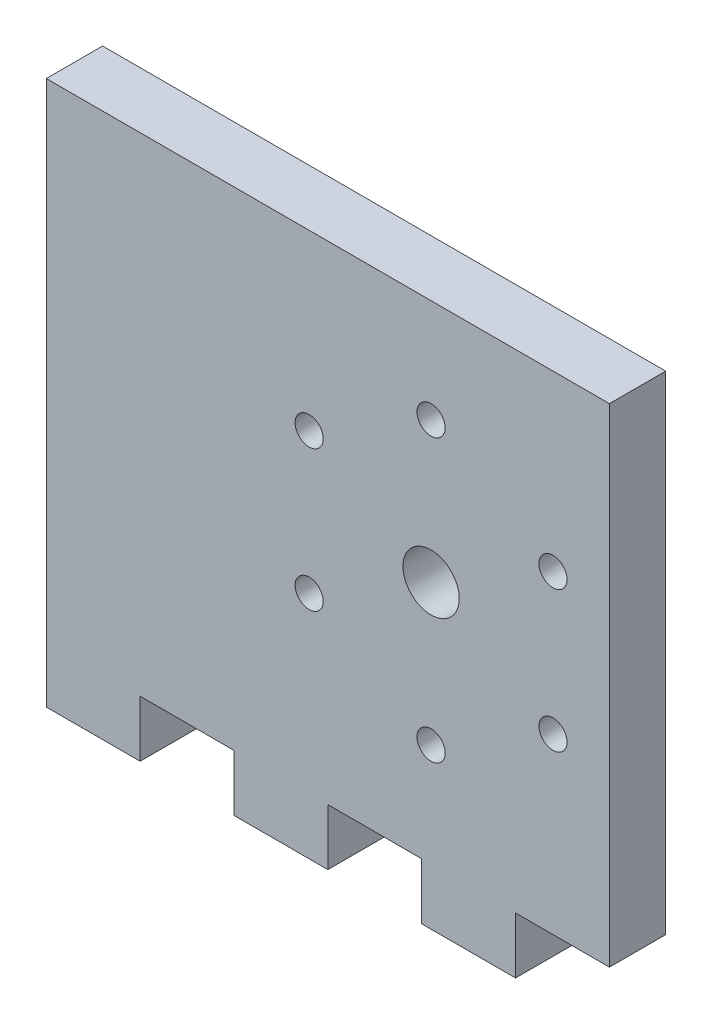
SolidWorks part; units mm, degrees
ref_plane "Alzado" through (0, 0, 0) normal (0, 0, 1) x (1, 0, 0)
ref_plane "Planta" through (0, 0, 0) normal (0, 1, 0) x (1, 0, 0)
ref_plane "Vista lateral" through (0, 0, 0) normal (1, 0, 0) x (0, 0, -1)
sketch "Sketch1" plane through (0, 0, 0) normal (0, 0, 1) x (1, 0, 0)
  line L0 (10, 0) -> (10, 3)
  line L1 (0, 0) -> (10, 0)
  line L2 (0, 0) -> (0, -29)
  line L3 (20.5, 0) -> (20.5, -26) construction
  line L4 (30, 0) -> (30, -26)
  line L5 (0, 0) -> (30, -26) construction
  line L6 (20.5, -13) -> (30, -13) construction
  line L7 (10, 3) -> (15, 3)
  line L8 (15, 3) -> (15, 0)
  line L9 (20, 0) -> (20, 3)
  line L10 (20, 3) -> (25, 3)
  line L11 (25, 3) -> (25, 0)
  line L12 (10, -26) -> (10, -29)
  line L13 (10, -29) -> (15, -29)
  line L14 (15, -29) -> (15, -26)
  line L15 (20, -29) -> (25, -29)
  line L16 (25, -29) -> (25, -26)
  line L17 (20, -29) -> (20, -26)
  line L18 (15, 0) -> (20, 0)
  line L19 (25, 0) -> (30, 0)
  line L20 (25, -26) -> (30, -26)
  line L21 (15, -26) -> (20, -26)
  line L23 (0, -29) -> (5, -29)
  line L24 (5, -29) -> (5, -26)
  line L25 (5, -26) -> (10, -26)
  circle A0 centre (20.5, -13) radius 7.5 construction
  circle A1 centre (20.5, -5.5) radius 0.75
  circle A2 centre (26.9952, -9.25) radius 0.75
  circle A3 centre (26.9952, -16.75) radius 0.75
  circle A4 centre (20.5, -20.5) radius 0.75
  circle A5 centre (14.0048, -16.75) radius 0.75
  circle A6 centre (14.0048, -9.25) radius 0.75
  circle A7 centre (20.5, -13) radius 1.5
  point P0 (0, 0)
  point P43 (20.5, -13)
  dimension "D7" = 15
  dimension "D8" = 1.5
  dimension "D10" = 3
  dimension "D1" = 30
  dimension "D2" = 5
  dimension "D3" = 3
  dimension "D4" = 29
  dimension "D5" = 3
  dimension "D6" = 9.5
  dimension "D9" = 6
extrude "Boss-Extrude1" add sketch "Sketch1" along normal blind 3
sketch "Croquis1" plane through (0, 0, 3) normal (0, 0, 1) x (1, 0, 0)
  line L1 (10, 0) -> (25, 0)
  line L2 (10, 0) -> (10, 6.7189)
  line L3 (10, 6.7189) -> (25, 6.7189)
  line L4 (25, 0) -> (25, 6.7189)
  point P5 (25, 3.3595)
  dimension "D1" = 6.7189
  dimension "D2" = 15
extrude "Cortar-Extruir1" cut sketch "Croquis1" against normal up to next
